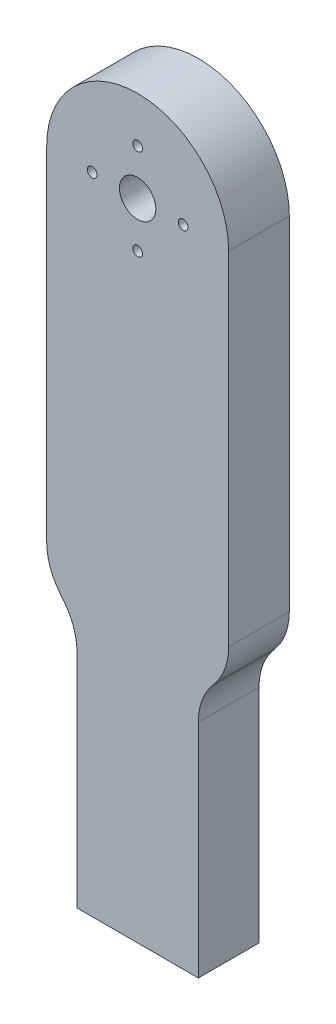
SolidWorks part; units mm, degrees
ref_plane "Plan de face" through (0, 0, 0) normal (0, 0, 1) x (1, 0, 0)
ref_plane "Plan de dessus" through (0, 0, 0) normal (0, 1, 0) x (1, 0, 0)
ref_plane "Plan de droite" through (0, 0, 0) normal (1, 0, 0) x (0, 0, -1)
sketch "Esquisse1" plane through (0, 0, 0) normal (0, 0, 1) x (1, 0, 0)
  line L0 (0, 0) -> (0, 74.7857) construction
  line L1 (-15, 13.5) -> (-15, -43.0103)
  line L2 (15, 13.5) -> (15, -43.0103)
  line L3 (-10, -92.7914) -> (10, -92.7914)
  line L24 (-12.8288, -49.232) -> (-12.1712, -50.0594)
  line L25 (-10, -56.2812) -> (-10, -92.7914)
  line L26 (10, -56.2812) -> (10, -92.7914)
  line L27 (12.8288, -49.232) -> (12.1712, -50.0594)
  circle A4 centre (-0.0053, 13.4988) radius 7.5
  arc A5 (-15, 13.5) -> (15, 13.5) centre (0, 13.5) cw
  circle A6 centre (-0.0053, 5.9988) radius 0.8
  circle A7 centre (-7.5053, 13.4988) radius 0.8
  circle A8 centre (-0.0053, 20.9988) radius 0.8
  circle A9 centre (7.4947, 13.4988) radius 0.8
  circle A10 centre (-0.0053, 13.4988) radius 3
  arc A11 (15, -43.0103) -> (12.8288, -49.232) centre (5, -43.0103) cw
  arc A12 (10, -56.2812) -> (12.1712, -50.0594) centre (20, -56.2812) cw
  arc A13 (-12.1712, -50.0594) -> (-10, -56.2812) centre (-20, -56.2812) cw
  arc A14 (-15, -43.0103) -> (-12.8288, -49.232) centre (-5, -43.0103) ccw
  point P8 (0, 0)
  point P21 (-0.0053, 13.4988)
  point P22 (-0.0053, 13.4988)
  point P24 (15, -46.5)
  point P27 (10, -52.7914)
  point P30 (-10, -52.7914)
  point P34 (-15, -46.5)
  dimension "D3" = 15
  dimension "D4" = 1.6
  dimension "D5" = 6
  dimension "D6" = 10
  dimension "D1" = 15
  dimension "D2" = 60
  dimension "D12" = 5
  dimension "D13" = 40
extrude "Boss.-Extru.1" add sketch "Esquisse1" along normal mid plane 10
